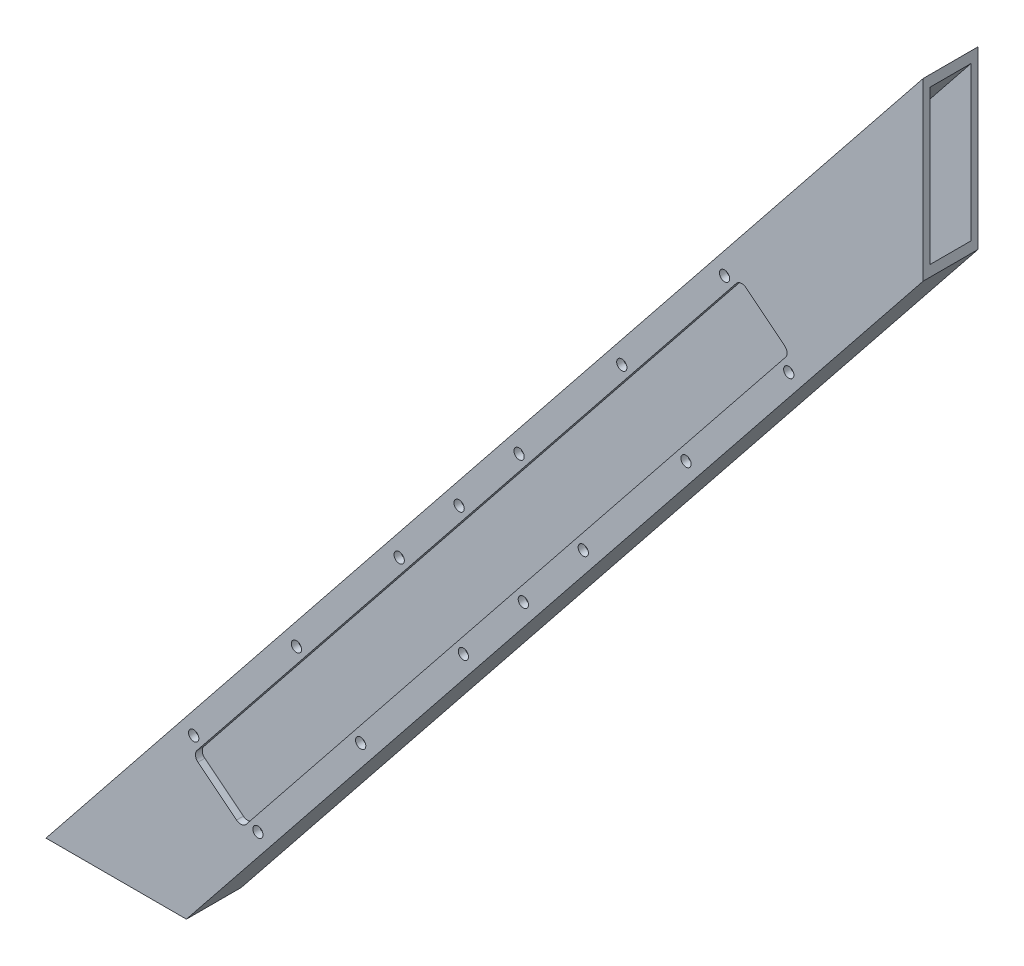
SolidWorks part; units mm, degrees
material "6063-T1"
ref_plane "Front Plane" through (0, 0, 0) normal (0, 0, 1) x (1, 0, 0)
ref_plane "Top Plane" through (0, 0, 0) normal (0, 1, 0) x (1, 0, 0)
ref_plane "Right Plane" through (0, 0, 0) normal (1, 0, 0) x (0, 0, -1)
sketch "Sketch1" plane through (0, 0, 0) normal (0, 0, 1) x (1, 0, 0)
  line L0 (0, 0) -> (406.4, 508)
  line L1 (406.4, 508) -> (406.4, 426.6803)
  line L2 (406.4, 426.6803) -> (65.0557, 0)
  line L3 (65.0557, 0) -> (0, 0)
  dimension "D1" = 406.4
  dimension "D2" = 508
  dimension "D3" = 50.8
extrude "Boss-Extrude1" add sketch "Sketch1" along normal blind 25.4
shell "Shell1" thickness 3.175
sketch "Sketch2" plane through (0, 0, 25.4) normal (0, 0, 1) x (1, 0, 0)
  line L0 (90.7409, 49.3868) -> (344.6169, 366.7319)
  line L1 (90.7409, 49.3868) -> (67.9317, 67.6342)
  line L2 (344.6169, 366.7319) -> (321.8077, 384.9793)
  line L3 (67.9317, 67.6342) -> (321.8077, 384.9793)
  line L4 (406.4, 508) -> (0, 0) construction
  line L5 (65.0557, 0) -> (406.4, 426.6803) construction
  line L6 (79.3363, 58.5105) -> (333.2123, 375.8556) construction
  line L7 (194.8697, 226.3067) -> (217.6789, 208.0594) construction
  line L8 (186.4402, 233.0503) -> (226.1084, 201.3158) construction
  circle A0 centre (68.4275, 75.3695) radius 2.3813
  circle A1 centre (116.0293, 134.8717) radius 2.3813
  circle A2 centre (163.6311, 194.3739) radius 2.3812
  circle A3 centre (193.3822, 170.573) radius 2.3812
  circle A4 centre (145.7804, 111.0708) radius 2.3813
  circle A5 centre (98.1786, 51.5686) radius 2.3813
  circle A6 centre (344.1211, 358.9966) radius 2.3813
  circle A7 centre (296.5193, 299.4944) radius 2.3813
  circle A8 centre (248.9176, 239.9922) radius 2.3812
  circle A9 centre (219.1664, 263.7931) radius 2.3812
  circle A10 centre (266.7682, 323.2953) radius 2.3813
  circle A11 centre (314.37, 382.7975) radius 2.3813
  circle A12 centre (191.3988, 229.0835) radius 2.3813
  circle A13 centre (221.1499, 205.2826) radius 2.3813
  point P43 (0, 0)
  point P44 (0, 0)
  dimension "D5" = 4.7625
  dimension "D9" = 4.7625
  dimension "D10" = 4.7625
  dimension "D1" = 406.4
  dimension "D2" = 29.21
  dimension "D3" = 10.795
  dimension "D4" = 57.15
  dimension "D6" = 6.35
  dimension "D7" = 6.35
  dimension "D11" = 6.35
  dimension "D12" = 6.35
  dimension "D8" = 3
extrude "Cut-Extrude1" cut sketch "Sketch2" against normal blind 5.08
fillet "Fillet1" radius 3.175 4 edges at (321.8077, 384.9793, 23.8125) (344.6169, 366.7319, 23.8125) (90.7409, 49.3868, 23.8125) (67.9317, 67.6342, 23.8125)
